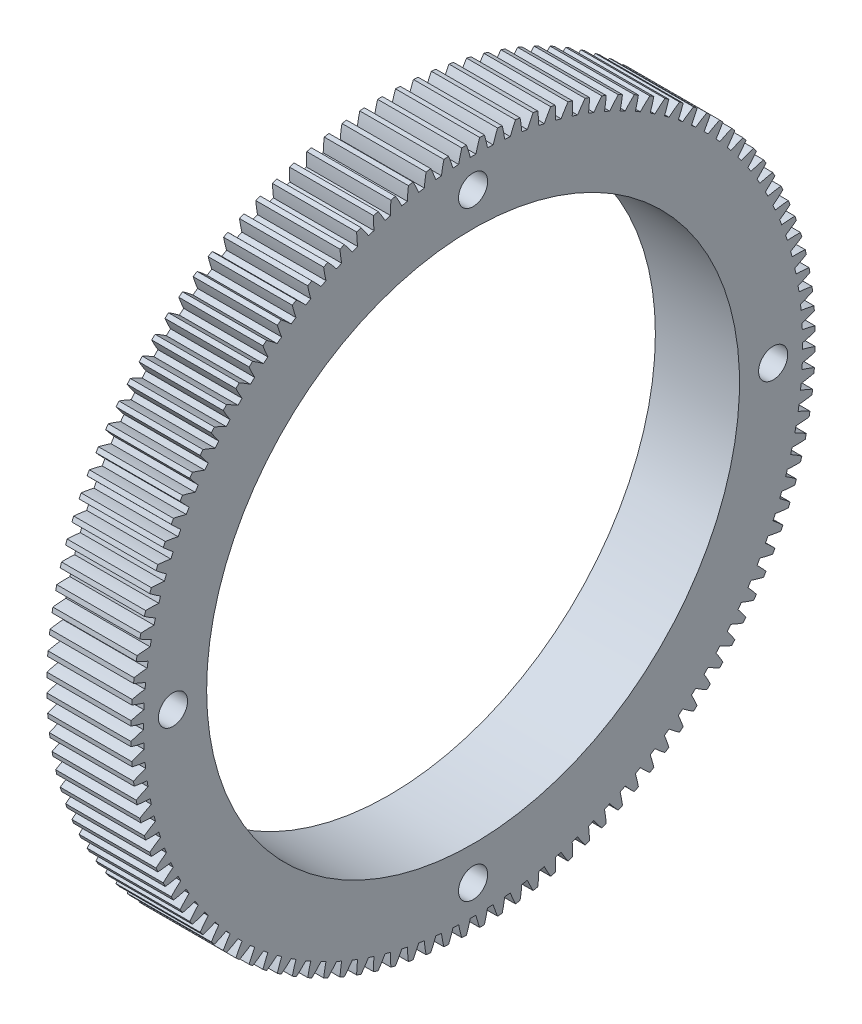
SolidWorks part; units mm, degrees
ref_plane "Plane1" through (0, 0, 0) normal (0, 0, 1) x (1, 0, 0)
ref_plane "Plane2" through (0, 0, 0) normal (0, 1, 0) x (1, 0, 0)
ref_plane "Plane3" through (0, 0, 0) normal (1, 0, 0) x (0, 0, -1)
other "Configuration Table"
sketch "HoldingSke" plane through (0, 0, 0) normal (0, 1, 0) x (1, 0, 0)
  line L0 (0, 0) -> (-0.5, -0.866)
  line L1 (-15, 0) -> (100, 0) construction
  line L2 (0, 0) -> (-2.1039, 2.3779)
  line L3 (0, 0) -> (-11.863, 4.5341)
  line L4 (0, 0) -> (-4.318, 7.479)
  line L5 (0, 0) -> (-46.8476, -17.4728)
  line L6 (0, 0) -> (-12.4344, -8.3896)
  line L7 (-2.1039, 2.3779) -> (8.6586, 51.2059)
  line L8 (-76.2, 54.61) -> (-69.8, 54.61)
  line L9 (-67.7845, 28.3722) -> (-49.3413, 33.142)
  line L10 (-76.2, 71.12) -> (104.1128, 71.12)
  line L11 (0, 0) -> (-15, 0)
  line L12 (-76.2, 101.6) -> (-76.162, 101.6)
  line L13 (24.9733, 27.94) -> (52.9518, 28.4284)
  line L14 (24.9733, 27.94) -> (24.9743, 27.94)
  line L15 (24.9733, 27.94) -> (100.4006, 29.5858)
  line L16 (-63.627, -1) -> (-12.827, -1)
  circle A0 centre (0, 0) radius 47.5
  circle A1 centre (0, 0) radius 37.5
  circle A2 centre (0, 0) radius 37.5
  circle A3 centre (0, 0) radius 47.5
  dimension "MHD" = 75
  dimension "Hub_dia" = 75
  dimension "Bore" = 95
  dimension "MBD" = 95
  dimension "Num_teeth" = 120
  dimension "Pitch" = 1
  dimension "Overall_len" = 50
  dimension "Show_teeth" = 120
  dimension "Thickness" = 15
  dimension "OAL" = 50.0001
  dimension "T_dim" = 6.4
  dimension "Ap" = 14.5
  dimension "H" = 19.05
  dimension "Pitch_radius" = 180.3128
  dimension "Width" = 15
  dimension "Backlash" = 0.038
  dimension "Addendum_fac" = 1
  dimension "Dedendum_fac" = 1.25
  dimension "Clearance_fac" = 0.25
  dimension "Dedendum_add" = 0.001
  dimension "Module" = 1
sketch "BasProSke" plane through (0, 0, 0) normal (0, 1, 0) x (1, 0, 0)
  line L0 (-10, 0) -> (60, 0) construction
  line L1 (0, 0) -> (0, 61)
  line L2 (0, 0) -> (15, 0)
  line L3 (15, 0) -> (15, 61)
  line L4 (15, 61) -> (0, 61)
  dimension "Thickness" = 15
  dimension "Diameter" = 122
revolve "Base-Revolve" add sketch "BasProSke" angle 360 about L0
sketch "TooCutSke" plane through (0, 0, 0) normal (1, 0, 0) x (0, 0, -1)
  line L1 (0, 0) -> (0, 107) construction
  line L2 (0, 0) -> (-0.8519, 59.994) construction
  line L3 (0, 0) -> (-3.141, 119.9503) construction
  line L4 (-0.8519, 59.994) -> (-1.5705, 59.9751) construction
  arc A0 (0.5076, 58.7468) -> (-0.5076, 58.7468) centre (0, 0) ccw
  arc A1 (1.1883, 61.0138) -> (-1.1883, 61.0138) centre (0, 0) ccw
  circle A2 centre (0, 0) radius 60 construction
  circle A3 centre (0, 0) radius 58.0889 construction
  arc A4 (-0.5076, 58.7468) -> (-1.1883, 61.0138) centre (-23.8061, 52.9866) ccw
  arc A5 (1.1883, 61.0138) -> (0.5076, 58.7468) centre (23.8061, 52.9866) ccw
  dimension "Root_dia" = 117.498
  dimension "Overcut_dia" = 122.0508
  dimension "Pitch_dia" = 120
  dimension "Base_dia" = 116.1777
  dimension "Flank_rad" = 24
  dimension "Half_ang" = 1.5
  dimension "Half_CT" = 0.7189
extrude "ToothCut" cut sketch "TooCutSke" along normal through all
fillet "Breaks" [suppressed] radius 0.02
fillet "RootFillets" [suppressed] radius 0.251
pattern_circular "TeethCuts" count 120 every 3 about axis through (-10, 0, 0) along (1, 0, 0) of "ToothCut", "RootFillets", "Breaks"
sketch "HubNeaOneSke" plane through (0, 0, 0) normal (-1, 0, 0) x (0, 0, 1)
  circle A0 centre (0, 0) radius 37.5
  dimension "Diameter" = 75
extrude "HubNearOne" [suppressed] add sketch "HubNeaOneSke" along normal blind 35.0001
sketch "HubNeaBotSke" plane through (0, 0, 0) normal (-1, 0, 0) x (0, 0, 1)
  circle A0 centre (0, 0) radius 37.5
  dimension "Diameter" = 75
extrude "HubNearBoth" [suppressed] add sketch "HubNeaBotSke" along normal blind 17.5
ref_plane "FarPln" through (15, 0, 0) normal (1, 0, 0) x (0, 0, -1)
sketch "HubFarSke" plane through (15, 0, 0) normal (1, 0, 0) x (0, 0, -1)
  circle A0 centre (0, 0) radius 37.5
  dimension "Diameter" = 75
extrude "HubFar" [suppressed] add sketch "HubFarSke" along normal blind 17.5
sketch "BorSke" plane through (0, 0, 0) normal (1, 0, 0) x (0, 0, -1)
  circle A0 centre (0, 0) radius 47.5
  dimension "Diameter" = 95
extrude "Bore" cut sketch "BorSke" along normal mid plane 100.0001
sketch "KeySke" plane through (0, 0, 0) normal (1, 0, 0) x (0, 0, -1)
  line L0 (-14, 0) -> (-14, 53.9)
  line L1 (-14, 53.9) -> (14, 53.9)
  line L2 (14, 53.9) -> (14, 0)
  line L3 (0, 0) -> (0, 34) construction
  line L4 (-14, 0) -> (14, 0)
  dimension "Offset" = 53.9
  dimension "Width" = 28
extrude "Keyway" [suppressed] cut sketch "KeySke" along normal mid plane 100.0001
pattern_circular "Keyway2" [suppressed] count 2 every 90 about axis through (-10, 0, 0) along (1, 0, 0)
sketch "草图1" plane through (0, 0, 0) normal (-1, 0, 0) x (0, 0, 1)
  line L0 (0, 0) -> (58.749, 0) construction
  line L1 (0, 0) -> (0, 58.749) construction
  line L2 (0, 0) -> (52.6951, 52.6951) construction
  arc A0 (58.7468, -0.5076) -> (58.7468, 0.5076) centre (0, 0) ccw construction
  arc A1 (0.5076, 58.7468) -> (-0.5076, 58.7468) centre (0, 0) ccw construction
  circle A2 centre (0, 53.5) radius 2.6
  circle A3 centre (53.5, 0) radius 2.6
  circle A4 centre (0, -53.5) radius 2.6
  circle A5 centre (-53.5, 0) radius 2.6
  dimension "D3" = 5.2
  dimension "D1" = 45
  dimension "D2" = 53.5
extrude "切除-拉伸1" cut sketch "草图1" against normal through all
equation "' \"Module@HoldingSke\" = 6.35"
equation "' \"Num_teeth@HoldingSke\" = 12"
equation "' \"Ap@HoldingSke\" =  20"
equation "' \"Ap@HoldingSke\" = 20"
equation "' \"Width@HoldingSke\" = 0.5 * 25.4"
equation "' \"Hub_dia@HoldingSke\"= 1 * 25.4"
equation "' \"Hub_dia@HoldingSke\" = 1 * 25.4"
equation "' \"Overall_len@HoldingSke\" = 1.0 * 25.4"
equation "' \"Bore@HoldingSke\" = 0.75 * 25.4"
equation "' \"T_dim@HoldingSke\" = 0.1 * 25.4"
equation "' \"Width@KeySke\" = 0.25 * 25.4"
equation "' \"Show_teeth@HoldingSke\" = 13"
equation "' \"Backlash@HoldingSke\" = 0.009 * 25.4"
equation "' \"Addendum_fac@HoldingSke\" = 1.0"
equation "' \"Dedendum_fac@HoldingSke\" = 1.25"
equation "' \"Dedendum_add@HoldingSke\" = 0.00005 * 25.4"
equation "' \"Clearance_fac@HoldingSke\" = 0.25"
equation "\"Pitch@HoldingSke\" = 1 / \"Module@HoldingSke\""
equation "\"Overcut_dia@TooCutSke\" = (\"Num_teeth@HoldingSke\" + 2 * \"Addendum_fac@HoldingSke\") / \"Pitch@HoldingSke\" + 0.002 * 25.4"
equation "\"Pitch_dia@TooCutSke\" = \"Num_teeth@HoldingSke\" / \"Pitch@HoldingSke\""
equation "\"Base_dia@TooCutSke\" = \"Num_teeth@HoldingSke\" / \"Pitch@HoldingSke\" * cos((\"Ap@HoldingSke\"  * 3.14159265 / 180))"
equation "\"Root_dia@TooCutSke\" = (\"Num_teeth@HoldingSke\" + 2) / \"Pitch@HoldingSke\" - 2 * (\"Addendum_fac@HoldingSke\" + \"Dedendum_fac@HoldingSke\") / \"Pitch@HoldingSke\" - \"Dedendum_add@HoldingSke\" * 2"
equation "\"Half_ang@TooCutSke\" = 180 / \"Num_teeth@HoldingSke\""
equation "\"Half_CT@TooCutSke\" = \"Num_teeth@HoldingSke\" / \"Pitch@HoldingSke\" * sin((3.14159265 / 2 / \"Num_teeth@HoldingSke\")) / 2 - 7 * \"Backlash@HoldingSke\" / 4"
equation "\"Flank_rad@TooCutSke\" = \"Num_teeth@HoldingSke\" / \"Pitch@HoldingSke\" / 5"
equation "\"Radius@RootFillets\" = \"Clearance_fac@HoldingSke\" / \"Pitch@HoldingSke\" + \"Dedendum_add@HoldingSke\""
equation "\"Break_rad@Breaks\" = 0.02 / \"Pitch@HoldingSke\""
equation "\"Thickness@HoldingSke\" = \"Width@HoldingSke\""
equation "\"OAL@HoldingSke\" = \"Thickness@HoldingSke\""
equation "\"MHD@HoldingSke\" = (\"Num_teeth@HoldingSke\" + 2) / \"Pitch@HoldingSke\" - 2 * (\"Addendum_fac@HoldingSke\" + \"Dedendum_fac@HoldingSke\")  / \"Pitch@HoldingSke\" - \"Dedendum_add@HoldingSke\" * 2"
equation "\"MBD@HoldingSke\" = (\"Num_teeth@HoldingSke\" + 2) / \"Pitch@HoldingSke\" - 2 * (\"Addendum_fac@HoldingSke\" + \"Dedendum_fac@HoldingSke\")  / \"Pitch@HoldingSke\" - \"Dedendum_add@HoldingSke\" * 2 - 0.002 * 25.4"
equation "\"MHD@HoldingSke\" = ((sgn( \"MHD@HoldingSke\" - \"Hub_dia@HoldingSke\" )-1)*( \"MHD@HoldingSke\" - \"Hub_dia@HoldingSke\" ))/-2+ \"Hub_dia@HoldingSke\""
equation "\"MBD@HoldingSke\" = ((sgn( \"MBD@HoldingSke\" - \"Bore@HoldingSke\" )-1)*( \"MBD@HoldingSke\" - \"Bore@HoldingSke\" ))/-2+ \"Bore@HoldingSke\""
equation "\"OAL@HoldingSke\" = ((sgn( \"OAL@HoldingSke\" - \"Overall_len@HoldingSke\" )+1)*( \"OAL@HoldingSke\" - \"Overall_len@HoldingSke\" ))/2 + \"Overall_len@HoldingSke\" + 0.000002 * 25.4"
equation "\"Num_teeth@TeethCuts\" = int( \"Show_teeth@HoldingSke\" ) + 1"
equation "\"Num_teeth@TeethCuts\" = ((sgn( \"Num_teeth@TeethCuts\" - \"Num_teeth@HoldingSke\" )-1)*( \"Num_teeth@TeethCuts\" - \"Num_teeth@HoldingSke\" ))/-2+ \"Num_teeth@HoldingSke\""
equation "\"Num_teeth@TeethCuts\" = ((sgn( \"Num_teeth@TeethCuts\" - 2.0)+1)*( \"Num_teeth@TeethCuts\" - 2.0))/2 +2.0"
equation "\"Angle@TeethCuts\" = 360.0 / \"Num_teeth@HoldingSke\""
equation "\"Diameter@BasProSke\" = (\"Num_teeth@HoldingSke\" + 2 * \"Addendum_fac@HoldingSke\") / \"Pitch@HoldingSke\""
equation "\"Thickness@BasProSke\"  = \"Thickness@HoldingSke\""
equation "' \"Fillet_rad@BasProSke\" =  \"Thickness@HoldingSke\" * 0.05"
equation "' \"Fillet_rad@BasProSke\" = \"Thickness@HoldingSke\" * 0.05"
equation "\"MHD@HoldingSke\" = ((sgn( \"MHD@HoldingSke\" - \"Root_dia@TooCutSke\" )-1)*( \"MHD@HoldingSke\" - \"Root_dia@TooCutSke\" ))/-2+ \"Root_dia@TooCutSke\""
equation "\"Diameter@HubNeaOneSke\" = \"MHD@HoldingSke\""
equation "\"Length@HubNearOne\" = \"OAL@HoldingSke\" - \"Thickness@BasProSke\""
equation "\"Diameter@HubNeaBotSke\" = \"MHD@HoldingSke\""
equation "\"Length@HubNearBoth\" = ( \"OAL@HoldingSke\" - \"Thickness@BasProSke\" ) / 2.0"
equation "\"Thickness@FarPln\" = \"Thickness@BasProSke\""
equation "\"Diameter@HubFarSke\" = \"MHD@HoldingSke\""
equation "\"Length@HubFar\" = ( \"OAL@HoldingSke\" - \"Thickness@BasProSke\" ) / 2.0"
equation "\"Diameter@BorSke\" = \"MBD@HoldingSke\""
equation "\"D1@Bore\" = \"OAL@HoldingSke\" * 2.0"
equation "\"D1@Keyway\" = \"OAL@HoldingSke\" * 2.0"
equation "\"Offset@KeySke\" = \"T_dim@HoldingSke\" + \"MBD@HoldingSke\" / 2.0"
